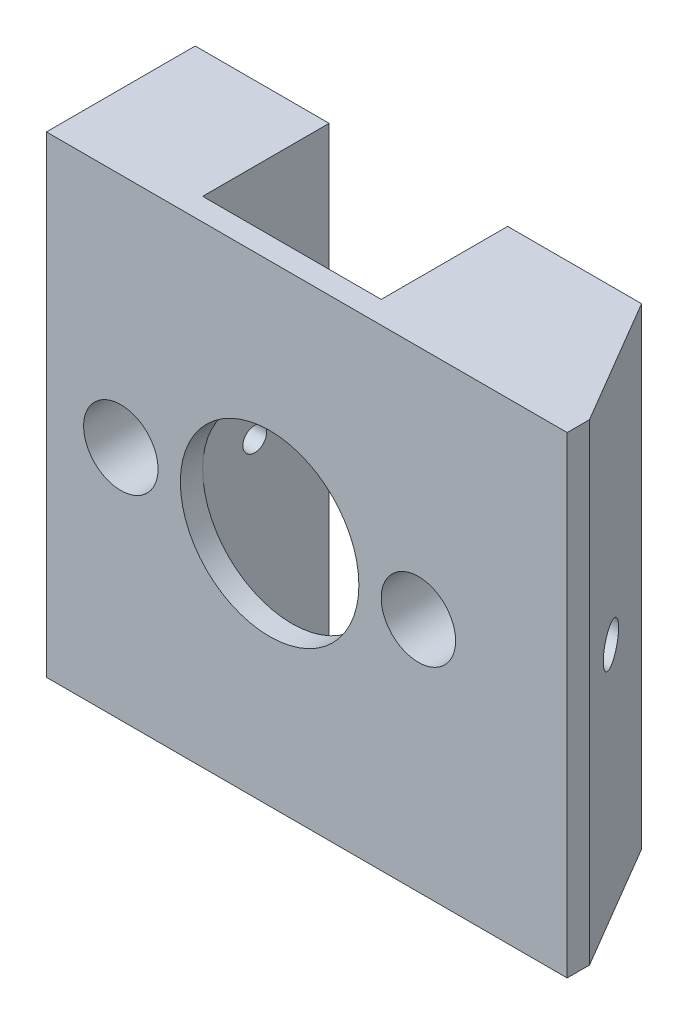
SolidWorks part; units mm, degrees
ref_plane "前视基准面" through (0, 0, 0) normal (0, 0, 1) x (1, 0, 0)
ref_plane "上视基准面" through (0, 0, 0) normal (0, 1, 0) x (1, 0, 0)
ref_plane "右视基准面" through (0, 0, 0) normal (1, 0, 0) x (0, 0, -1)
other "Configuration Table"
sketch "草图1" plane through (0, 0, 0) normal (0, 0, 1) x (1, 0, 0)
  line L0 (45, 81) -> (-15, 81) construction
  line L1 (45, 17.5) -> (27, 17.5)
  line L2 (45, 17.5) -> (45, 81)
  line L3 (45, 81) -> (27, 81)
  line L4 (-15, 17.5) -> (-15, 81)
  line L5 (45, 17.5) -> (-15, 81) construction
  line L6 (45, 81) -> (-15, 17.5) construction
  line L7 (3, 81) -> (-15, 81)
  line L9 (27, 17.5) -> (27, 81)
  line L11 (3, 17.5) -> (3, 81)
  line L12 (27, 17.5) -> (3, 81) construction
  line L13 (27, 81) -> (3, 17.5) construction
  line L14 (3, 17.5) -> (-15, 17.5)
  circle A0 centre (-5, 49.25) radius 5
  circle A2 centre (35, 49.25) radius 5
  point P0 (15, 49.25)
  dimension "D1" = 10
  dimension "D2" = 10
extrude "凸台-拉伸1" add sketch "草图1" along normal blind 17
ref_plane "基准面1" through (0, 0, 17) normal (0, 0, 1) x (1, 0, 0)
sketch "草图2" plane through (0, 0, 17) normal (0, 0, 1) x (1, 0, 0)
  line L1 (-15, 81) -> (45, 81)
  line L2 (-15, 81) -> (-15, 17.5)
  line L3 (-15, 17.5) -> (45, 17.5)
  line L4 (45, 81) -> (45, 17.5)
  circle A0 centre (35, 49.25) radius 5
  circle A1 centre (-5, 49.25) radius 5
  circle A2 centre (15, 49.25) radius 12
extrude "凸台-拉伸2" add sketch "草图2" along normal blind 3
sketch "草图3" plane through (45, 0, 0) normal (1, 0, 0) x (0, 0, -1)
  line L0 (-20, 17.5) -> (0, 17.5) construction
  line L1 (-20, 81) -> (-17, 81)
  line L2 (-20, 81) -> (-20, 17.5)
  line L3 (-20, 17.5) -> (-17, 17.5)
  line L4 (-17, 81) -> (-17, 17.5)
  dimension "D1" = 3
extrude "凸台-拉伸3" add sketch "草图3" along normal blind 10
sketch "草图4" plane through (0, 17.5, 0) normal (0, -1, 0) x (1, 0, 0)
  line L0 (55, 17) -> (45, 0)
rib "筋1" sketch "草图4" sketch "草图4" thickness 63.5 extrusion direction parallel to sketch draft on no parameters "D1"=63.5
ref_plane "基准面2" through (0, 0, 10) normal (0, 0, 1) x (1, 0, 0)
sketch "草图7" plane through (0, 0, 10) normal (0, 0, 1) x (1, 0, 0)
  line L0 (-15, 49.25) -> (1.5646, 49.25) construction
  line L1 (-15, 81) -> (-15, 17.5) construction
  line L2 (15, 61.25) -> (15, 37.25) construction
  line L3 (-14, 45.75) -> (-11, 45.75)
  line L4 (-14, 45.75) -> (-14, 52.75)
  line L5 (-14, 52.75) -> (-11, 52.75)
  line L6 (-11, 45.75) -> (-11, 52.75)
  line L7 (-14, 45.75) -> (-11, 52.75) construction
  line L8 (-14, 52.75) -> (-11, 45.75) construction
  line L9 (44, 52.75) -> (41, 45.75) construction
  line L10 (44, 45.75) -> (41, 52.75) construction
  line L11 (41, 45.75) -> (41, 52.75)
  line L12 (44, 52.75) -> (41, 52.75)
  line L13 (44, 45.75) -> (44, 52.75)
  line L14 (44, 45.75) -> (41, 45.75)
  circle A0 centre (-5, 49.25) radius 5 construction
  circle A1 centre (15, 49.25) radius 12 construction
  point P4 (-12.5, 49.25)
  point P9 (-10, 49.25)
  point P21 (42.5, 49.25)
  dimension "D1" = 3
  dimension "D2" = 7
  dimension "D3" = 2.5
extrude "切除-拉伸1" cut sketch "草图7" against normal mid plane 7
hole_wizard "孔1" positions "草图9" profile "草图10" legacy end condition through all
sketch "草图9" plane through (-15, 0, 0) normal (-1, 0, 0) x (0, 0, 1)
  line L0 (20, 49.25) -> (0, 49.25) construction
  line L1 (20, 81) -> (20, 17.5) construction
  line L2 (0, 81) -> (0, 17.5) construction
  point P0 (10, 49.25)
sketch "草图10" plane through (-15, 49.25, 10) normal (0, 1, 0) x (0, 0, 1)
  line L0 (0, 0) -> (0, 70)
  line L1 (0, 70) -> (1.6, 70)
  line L2 (1.6, 70) -> (1.6, 0)
  line L3 (1.6, 0) -> (0, 0)
  line L4 (0, 110) -> (0, -10) construction
  dimension "直径" = 3.2
  dimension "深度" = 70
ref_plane "基准面3" through (47, 0, 0) normal (-1, 0, 0) x (0, 0, 1)
sketch "草图13" plane through (47, 0, 0) normal (-1, 0, 0) x (0, 0, 1)
  circle A0 centre (10, 49.25) radius 2.5
  dimension "D1" = 5
extrude "切除-拉伸2" cut sketch "草图13" against normal blind 11
